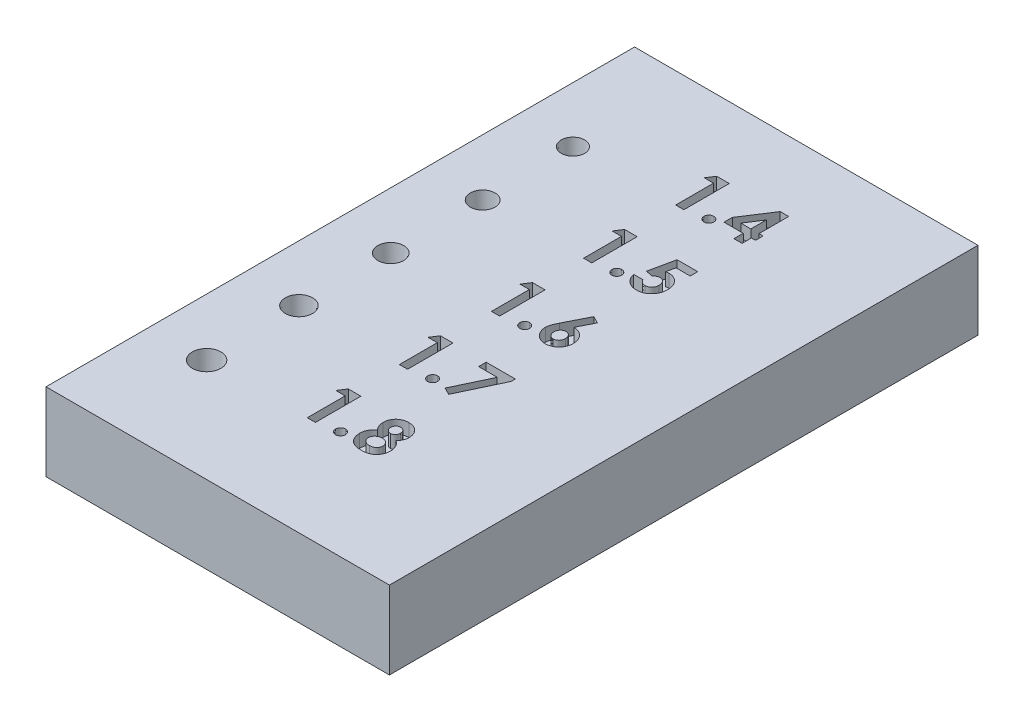
SolidWorks part; units mm, degrees
ref_plane "Front Plane" through (0, 0, 0) normal (0, 0, 1) x (1, 0, 0)
ref_plane "Top Plane" through (0, 0, 0) normal (0, 1, 0) x (1, 0, 0)
ref_plane "Right Plane" through (0, 0, 0) normal (1, 0, 0) x (0, 0, -1)
sketch "Sketch1" plane through (0, 0, 0) normal (0, 1, 0) x (1, 0, 0)
  line L1 (0, 0) -> (26.4544, 0)
  line L2 (0, 0) -> (0, 45.3357)
  line L3 (0, 45.3357) -> (26.4544, 45.3357)
  line L4 (26.4544, 0) -> (26.4544, 45.3357)
  point P4 (35, 28.311)
  dimension "D1" = 26.4544
  dimension "D2" = 45.3357
extrude "Boss-Extrude1" add sketch "Sketch1" along normal blind 6
sketch "Sketch4" plane through (0, 6, 0) normal (0, 1, 0) x (1, 0, 0)
  line L0 (4.3357, 45.3357) -> (4.3357, 0) construction
  line L1 (26.4544, 45.3357) -> (0, 45.3357) construction
  line L2 (0, 0) -> (26.4544, 0) construction
  line L3 (0, 36.3761) -> (17.7357, 36.3761) construction
  line L4 (0, 45.3357) -> (0, 0) construction
  line L5 (0, 29.2821) -> (17.7357, 29.2821) construction
  line L6 (0, 22.1881) -> (17.7357, 22.1881) construction
  line L7 (0, 15.094) -> (17.7357, 15.094) construction
  line L8 (0, 8) -> (17.7357, 8) construction
  text T0 "<b>1.4</b>"
  text T1 "<b>1.5</b>"
  text T2 "<b>1.6</b>"
  text T3 "<b>1.7</b>"
  text T4 "<b>1.8</b>"
  point P10 (0, 36.3761)
  dimension "D1" = 5
  dimension "D2" = 8
extrude "Cut-Extrude1" cut sketch "Sketch4" against normal blind 1
hole_wizard "Tap Drill for M2 Tap1" positions "Sketch2" profile "Sketch3" hole size "M2" standard "ISO" end condition through all
sketch "Sketch2" plane through (0, 6, 0) normal (0, 1, 0) x (1, 0, 0)
  point P0 (4.2741, 36.3147)
  point P3 (0, 0)
  point P4 (4.3272, 25.9614)
  point P5 (4.2741, 36.3147)
sketch "Sketch3" plane through (4.2741, 6, -36.3147) normal (1, 0, 0) x (0, 0, 1)
  line L0 (0, 0) -> (0, 6)
  line L1 (0, 6) -> (0.7, 6)
  line L2 (0.7, 6) -> (0.7, 2.0771)
  line L3 (0.7, 2.0771) -> (0.9, 0)
  line L5 (0.9, 0) -> (0, 0)
  line L6 (-0.7, 2.0771) -> (-0.9, 0) construction
  line L11 (0, -6.35) -> (0, 107.95) construction
  dimension "Thru Hole Dia." = 1.4
  dimension "Thru Hole Depth" = 6
  dimension "Near C'Sink Dia." = 1.8
  dimension "Near C'Sink Angle" = 11
hole_wizard "Tap Drill for M2 Tap2" positions "Sketch5" profile "Sketch6" hole size "M2" standard "ISO" end condition through all
sketch "Sketch5" plane through (0, 6, 0) normal (0, 1, 0) x (1, 0, 0)
  point P0 (4.3597, 29.2757)
sketch "Sketch6" plane through (4.3597, 6, -29.2757) normal (1, 0, 0) x (0, 0, 1)
  line L0 (0, 0) -> (0, 6)
  line L1 (0, 6) -> (0.75, 6)
  line L2 (0.75, 6) -> (0.75, 2.0771)
  line L3 (0.75, 2.0771) -> (0.95, 0)
  line L5 (0.95, 0) -> (0, 0)
  line L6 (-0.75, 2.0771) -> (-0.95, 0) construction
  line L11 (0, -6.35) -> (0, 107.95) construction
  dimension "Thru Hole Dia." = 1.5
  dimension "Thru Hole Depth" = 6
  dimension "Near C'Sink Dia." = 1.9
  dimension "Near C'Sink Angle" = 11
hole_wizard "Tap Drill for M2 Tap3" positions "Sketch7" profile "Sketch8" hole size "M2" standard "ISO" end condition through all
sketch "Sketch7" plane through (0, 6, 0) normal (0, 1, 0) x (1, 0, 0)
  point P0 (4.3566, 22.1982)
sketch "Sketch8" plane through (4.3566, 6, -22.1982) normal (1, 0, 0) x (0, 0, 1)
  line L0 (0, 0) -> (0, 6)
  line L1 (0, 6) -> (0.8, 6)
  line L2 (0.8, 6) -> (0.8, 2.0771)
  line L3 (0.8, 2.0771) -> (1, 0)
  line L5 (1, 0) -> (0, 0)
  line L6 (-0.8, 2.0771) -> (-1, 0) construction
  line L11 (0, -6.35) -> (0, 107.95) construction
  dimension "Thru Hole Dia." = 1.6
  dimension "Thru Hole Depth" = 6
  dimension "Near C'Sink Dia." = 2
  dimension "Near C'Sink Angle" = 11
hole_wizard "Tap Drill for M2 Tap4" positions "Sketch9" profile "Sketch10" hole size "M2" standard "ISO" end condition through all
sketch "Sketch9" plane through (0, 6, 0) normal (0, 1, 0) x (1, 0, 0)
  point P0 (4.3299, 15.1545)
sketch "Sketch10" plane through (4.3299, 6, -15.1545) normal (1, 0, 0) x (0, 0, 1)
  line L0 (0, 0) -> (0, 6)
  line L1 (0, 6) -> (0.85, 6)
  line L2 (0.85, 6) -> (0.85, 2.0771)
  line L3 (0.85, 2.0771) -> (1.05, 0)
  line L5 (1.05, 0) -> (0, 0)
  line L6 (-0.85, 2.0771) -> (-1.05, 0) construction
  line L11 (0, -6.35) -> (0, 107.95) construction
  dimension "Thru Hole Dia." = 1.7
  dimension "Thru Hole Depth" = 6
  dimension "Near C'Sink Dia." = 2.1
  dimension "Near C'Sink Angle" = 11
hole_wizard "Tap Drill for M2 Tap5" positions "Sketch11" profile "Sketch12" hole size "M2" standard "ISO" end condition through all
sketch "Sketch11" plane through (0, 6, 0) normal (0, 1, 0) x (1, 0, 0)
  point P0 (4.4077, 7.9663)
sketch "Sketch12" plane through (4.4077, 6, -7.9663) normal (1, 0, 0) x (0, 0, 1)
  line L0 (0, 0) -> (0, 6)
  line L1 (0, 6) -> (0.9, 6)
  line L2 (0.9, 6) -> (0.9, 2.0771)
  line L3 (0.9, 2.0771) -> (1.1, 0)
  line L5 (1.1, 0) -> (0, 0)
  line L6 (-0.9, 2.0771) -> (-1.1, 0) construction
  line L11 (0, -6.35) -> (0, 107.95) construction
  dimension "Thru Hole Dia." = 1.8
  dimension "Thru Hole Depth" = 6
  dimension "Near C'Sink Dia." = 2.2
  dimension "Near C'Sink Angle" = 11
